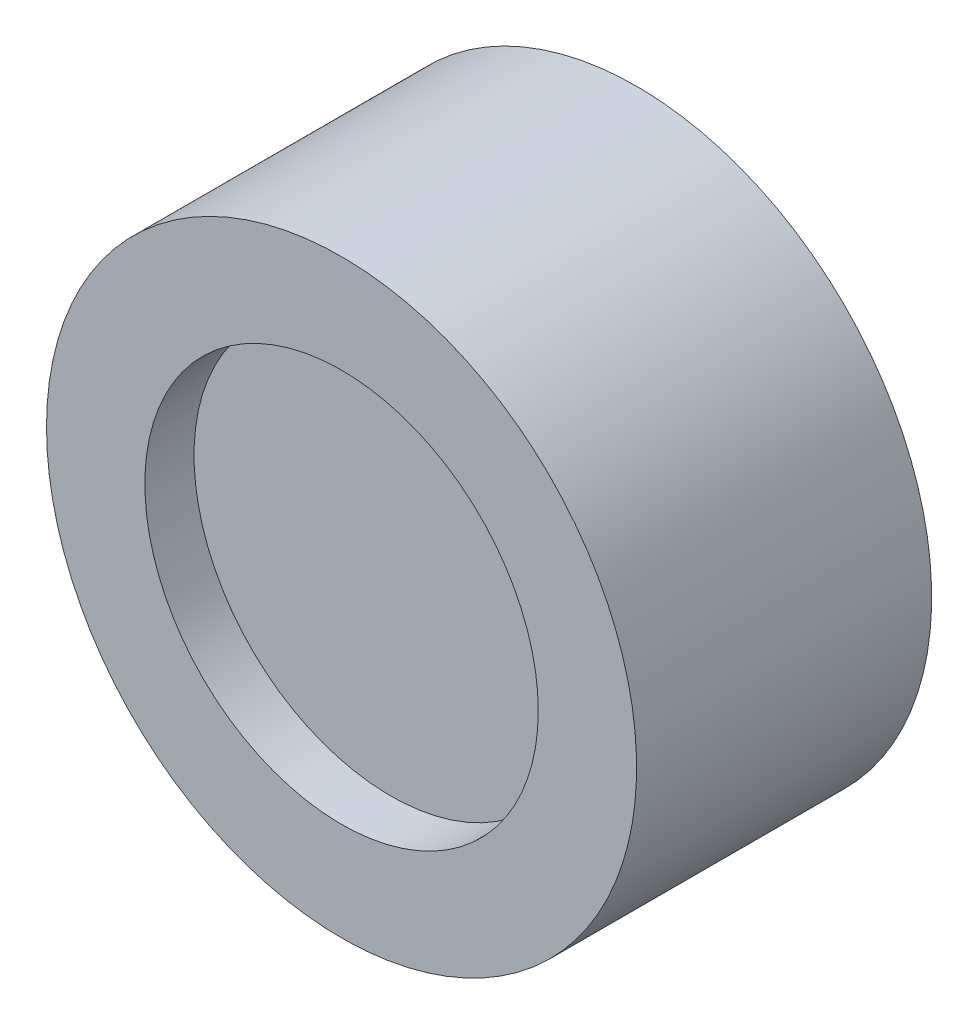
SolidWorks part; units mm, degrees
material "Oak"
ref_plane "Front" through (0, 0, 0) normal (0, 0, 1) x (1, 0, 0)
ref_plane "Top" through (0, 0, 0) normal (0, 1, 0) x (1, 0, 0)
ref_plane "Right" through (0, 0, 0) normal (1, 0, 0) x (0, 0, -1)
sketch "Sketch1" plane through (0, 0, 0) normal (0, 0, 1) x (1, 0, 0)
  circle A0 centre (0, 0) radius 38.1
  dimension "D1" = 76.2
extrude "Boss-Extrude1" add sketch "Sketch1" along normal blind 38.1
sketch "Sketch2" plane through (0, 0, 38.1) normal (0, 0, 1) x (1, 0, 0)
  circle A0 centre (0, 0) radius 25.4
  dimension "D1" = 50.8
extrude "Cut-Extrude1" cut sketch "Sketch2" against normal blind 6.35
